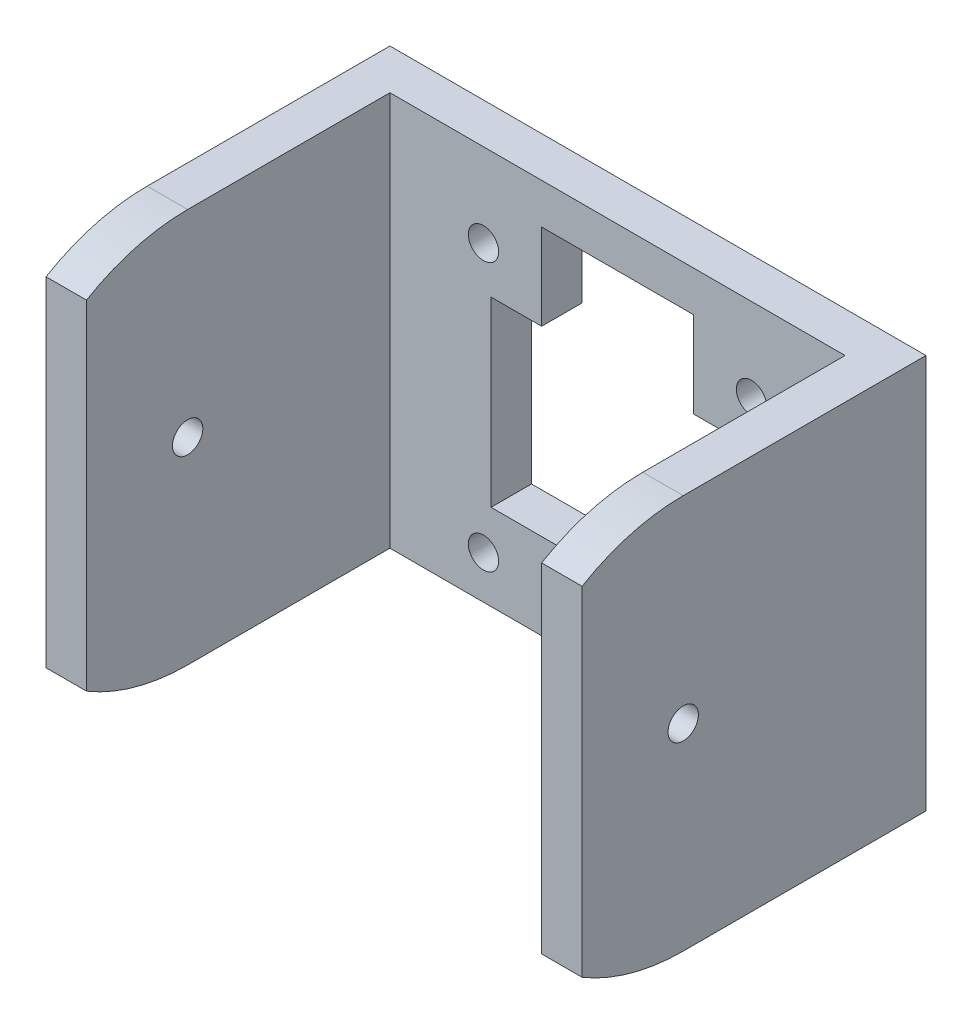
SolidWorks part; units mm, degrees
ref_plane "前视基准面" through (0, 0, 0) normal (0, 0, 1) x (1, 0, 0)
ref_plane "上视基准面" through (0, 0, 0) normal (0, 1, 0) x (1, 0, 0)
ref_plane "右视基准面" through (0, 0, 0) normal (1, 0, 0) x (0, 0, -1)
sketch "草图1" plane through (0, 0, 0) normal (0, 0, 1) x (1, 0, 0)
  line L0 (-93.1859, 43.6179) -> (-93.1859, 8.6179) construction
  line L1 (-110.6859, 43.6179) -> (-75.6859, 43.6179)
  line L2 (-110.6859, 43.6179) -> (-110.6859, 8.6179)
  line L3 (-110.6859, 8.6179) -> (-75.6859, 8.6179)
  line L4 (-75.6859, 43.6179) -> (-75.6859, 8.6179)
  line L5 (-106.4359, 26.1179) -> (-93.1859, 26.1179) construction
  line L6 (-79.9359, 12.8679) -> (-106.4359, 12.8679) construction
  line L7 (-79.9359, 12.8679) -> (-79.9359, 39.3679) construction
  line L8 (-79.9359, 39.3679) -> (-106.4359, 39.3679) construction
  line L9 (-106.4359, 12.8679) -> (-106.4359, 39.3679) construction
  line L10 (-79.9359, 12.8679) -> (-106.4359, 39.3679) construction
  line L11 (-79.9359, 39.3679) -> (-106.4359, 12.8679) construction
  line L12 (-105.6859, 17.1179) -> (-80.6859, 17.1179)
  line L13 (-105.6859, 17.1179) -> (-105.6859, 35.1179)
  line L14 (-105.6859, 35.1179) -> (-80.6859, 35.1179)
  line L15 (-80.6859, 17.1179) -> (-80.6859, 35.1179)
  line L16 (-105.6859, 17.1179) -> (-80.6859, 35.1179) construction
  line L17 (-105.6859, 35.1179) -> (-80.6859, 17.1179) construction
  circle A0 centre (-106.4359, 39.3679) radius 1.5
  circle A1 centre (-79.9359, 12.8679) radius 1.5
  circle A2 centre (-79.9359, 39.3679) radius 1.5
  circle A3 centre (-106.4359, 12.8679) radius 1.5
  point P6 (-93.1859, 26.1179)
  dimension "D4" = 3
  dimension "D1" = 35
  dimension "D2" = 35
  dimension "D3" = 26.5
  dimension "D5" = 25
  dimension "D6" = 18
  dimension "D7" = 8.5
extrude "凸台-拉伸2" add sketch "草图1" along normal blind 4
sketch "草图2" plane through (0, 0, 4) normal (0, 0, 1) x (1, 0, 0)
  line L0 (-93.1859, 43.6179) -> (-93.1859, 35.1179) construction
  line L1 (-75.6859, 43.6179) -> (-110.6859, 43.6179) construction
  line L2 (-80.6859, 35.1179) -> (-105.6859, 35.1179) construction
  line L3 (-100.6859, 43.6179) -> (-85.6859, 43.6179)
  line L4 (-100.6859, 43.6179) -> (-100.6859, 34.6179)
  line L5 (-85.6859, 43.6179) -> (-85.6859, 34.6179)
  line L6 (-100.6859, 34.6179) -> (-85.6859, 34.6179)
  line L7 (-100.6859, 43.6179) -> (-85.6859, 34.6179) construction
  line L8 (-85.6859, 43.6179) -> (-100.6859, 34.6179) construction
  point P6 (-93.1859, 39.6306)
  point P7 (-93.1859, 39.1179)
  dimension "D1" = 15
  dimension "D2" = 9
  dimension "D3" = 0
extrude "切除-拉伸1" cut sketch "草图2" against normal up to surface (4 mm away) up to face at (-107.9359, 12.8679, 0)
sketch "草图3" plane through (0, 43.6179, 0) normal (0, 1, 0) x (1, 0, 0)
  line L1 (-110.6859, 0) -> (-75.6859, 0)
  line L2 (-110.6859, 0) -> (-110.6859, -4)
  line L3 (-110.6859, -4) -> (-75.6859, -4)
  line L4 (-75.6859, 0) -> (-75.6859, -4)
extrude "凸台-拉伸3" add sketch "草图3" along normal blind 4
sketch "草图4" plane through (-75.6859, 0, 0) normal (1, 0, 0) x (0, 0, -1)
  line L4 (0, 8.6179) -> (0, 47.6179)
  line L5 (0, 47.6179) -> (-4, 47.6179)
  line L6 (-4, 47.6179) -> (-4, 8.6179)
  line L7 (-4, 8.6179) -> (0, 8.6179)
  line L8 (0, 8.6179) -> (0, 47.6179)
  line L9 (0, 47.6179) -> (-4, 47.6179)
  line L10 (-4, 47.6179) -> (-4, 8.6179)
  line L11 (-4, 8.6179) -> (0, 8.6179)
  dimension "D1" = 0
extrude "凸台-拉伸4" add sketch "草图4" along normal blind 9
sketch "草图5" plane through (-110.6859, 0, 0) normal (-1, 0, 0) x (0, 0, 1)
  line L4 (0, 47.6179) -> (0, 8.6179)
  line L5 (0, 8.6179) -> (4, 8.6179)
  line L6 (4, 8.6179) -> (4, 47.6179)
  line L7 (4, 47.6179) -> (0, 47.6179)
  line L8 (0, 47.6179) -> (0, 8.6179)
  line L9 (0, 8.6179) -> (4, 8.6179)
  line L10 (4, 8.6179) -> (4, 47.6179)
  line L11 (4, 47.6179) -> (0, 47.6179)
  dimension "D1" = 0
extrude "凸台-拉伸5" add sketch "草图5" along normal blind 9
sketch "草图6" plane through (0, 0, 4) normal (0, 0, 1) x (1, 0, 0)
  line L0 (-119.6859, 8.6179) -> (-66.6859, 8.6179) construction
  line L1 (-119.6859, 47.6179) -> (-115.6859, 47.6179)
  line L2 (-119.6859, 47.6179) -> (-119.6859, 8.6179)
  line L3 (-119.6859, 8.6179) -> (-115.6859, 8.6179)
  line L4 (-115.6859, 47.6179) -> (-115.6859, 8.6179)
  line L5 (-93.1859, 47.6179) -> (-93.1859, 8.6179) construction
  line L6 (-119.6859, 47.6179) -> (-66.6859, 47.6179) construction
  line L7 (-70.6859, 47.6179) -> (-70.6859, 8.6179)
  line L8 (-66.6859, 8.6179) -> (-70.6859, 8.6179)
  line L9 (-66.6859, 47.6179) -> (-66.6859, 8.6179)
  line L10 (-66.6859, 47.6179) -> (-70.6859, 47.6179)
  dimension "D1" = 4
extrude "凸台-拉伸6" add sketch "草图6" along normal blind 30
sketch "草图7" plane through (-119.6859, 0, 0) normal (-1, 0, 0) x (0, 0, 1)
  line L0 (24, 47.6179) -> (24, 8.6179) construction
  line L1 (34, 47.6179) -> (0, 47.6179) construction
  line L2 (0, 8.6179) -> (34, 8.6179) construction
  line L3 (34, 47.6179) -> (34, 8.6179) construction
  circle A0 centre (24, 28.1179) radius 1.5
  dimension "D2" = 3
  dimension "D1" = 10
extrude "切除-拉伸2" cut sketch "草图7" against normal up to surface (53 mm away) up to face at (-66.6859, 28.1179, 17)
sketch "草图9" plane through (-119.6859, 0, 0) normal (-1, 0, 0) x (0, 0, 1)
  line L4 (34, 47.6179) -> (0, 47.6179)
  line L5 (0, 47.6179) -> (0, 8.6179)
  line L6 (0, 8.6179) -> (34, 8.6179)
  line L7 (34, 8.6179) -> (34, 47.6179)
  line L8 (34, 47.6179) -> (0, 47.6179)
  line L9 (0, 47.6179) -> (0, 8.6179)
  line L10 (0, 8.6179) -> (34, 8.6179)
  line L11 (34, 8.6179) -> (34, 47.6179)
  circle A0 centre (24, 28.1179) radius 19.5
  line M7 (34, 47.6179) -> (0, 47.6179)
  line M10 (34, 8.6179) -> (34, 47.6179)
  dimension "D1" = 0
extrude "切除-拉伸3" cut sketch "草图9" against normal up to surface (53 mm away) contours A0 M10 M7 | A0 L10 M10 up to face at (-66.6859, 29.6179, 24)
